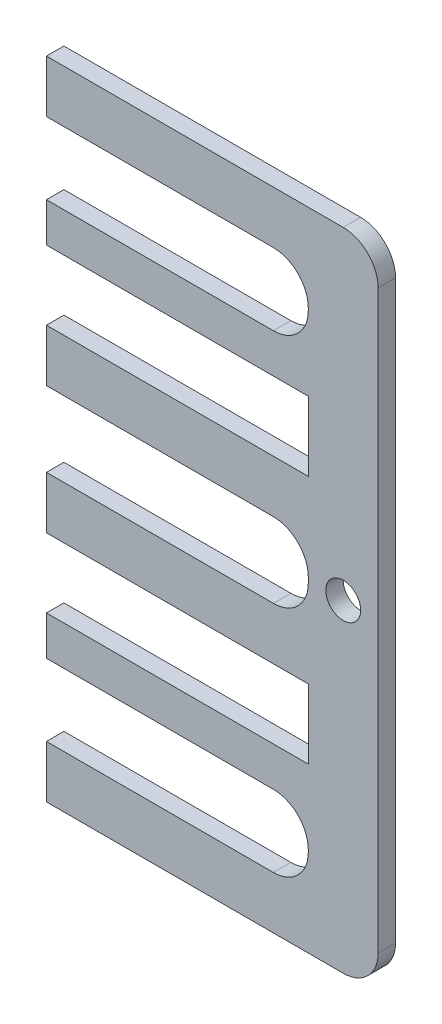
SolidWorks part; units mm, degrees
ref_plane "正面" through (0, 0, 0) normal (0, 0, 1) x (1, 0, 0)
ref_plane "平面" through (0, 0, 0) normal (0, 1, 0) x (1, 0, 0)
ref_plane "右側面" through (0, 0, 0) normal (1, 0, 0) x (0, 0, -1)
sketch "ｽｹｯﾁ1" plane through (0, 0, 0) normal (0, 0, 1) x (1, 0, 0)
  line L0 (-38, -31) -> (-38, -37)
  line L1 (0, 37) -> (0, -37)
  line L2 (0, -37) -> (-38, -37)
  line L3 (-54.551, 0) -> (64.3943, 0) construction
  line L4 (-38, -31) -> (-8, -31)
  line L5 (-8, -31) -> (-8, -22.75)
  line L6 (-8, -22.75) -> (-38, -22.75)
  line L7 (-38, -22.75) -> (-38, -18.25)
  line L8 (-38, -18.25) -> (-8, -18.25)
  line L9 (-8, -18.25) -> (-8, -10.3)
  line L10 (-8, -10.3) -> (-38, -10.3)
  line L11 (-38, -10.3) -> (-38, -4.3)
  line L12 (-38, -4.3) -> (-8, -4.3)
  line L13 (-8, -4.3) -> (-8, 4.3)
  line L14 (-38, 4.3) -> (-8, 4.3)
  line L15 (-38, 10.3) -> (-38, 4.3)
  line L16 (-8, 10.3) -> (-38, 10.3)
  line L17 (-8, 18.25) -> (-8, 10.3)
  line L18 (-38, 18.25) -> (-8, 18.25)
  line L19 (-38, 22.75) -> (-38, 18.25)
  line L20 (-8, 22.75) -> (-38, 22.75)
  line L21 (-8, 31) -> (-8, 22.75)
  line L22 (-38, 31) -> (-8, 31)
  line L23 (0, 37) -> (-38, 37)
  line L24 (-38, 31) -> (-38, 37)
  line L25 (-8, -26.875) -> (-55.736, -26.875) construction
  circle A0 centre (-4, 0) radius 2
  point P19 (-8, 0)
  point P30 (0, 0)
  point P33 (-3.7736, 0)
  dimension "D11" = 4
  dimension "D1" = 37
  dimension "D2" = 6
  dimension "D3" = 8.25
  dimension "D4" = 4.5
  dimension "D5" = 4.3
  dimension "D6" = 30
  dimension "D7" = 8
  dimension "D8" = 6
  dimension "D9" = 26.875
  dimension "D10" = 4
extrude "ﾎﾞｽ - 押し出し1" add sketch "ｽｹｯﾁ1" along normal blind 2
fillet "ﾌｨﾚｯﾄ1" radius 4 8 edges at (-8, 22.75, 1) (-8, 31, 1) (-8, -4.3, 1) (-8, 4.3, 1) (-8, -31, 1) (-8, -22.75, 1) (0, -37, 1) (0, 37, 1)
